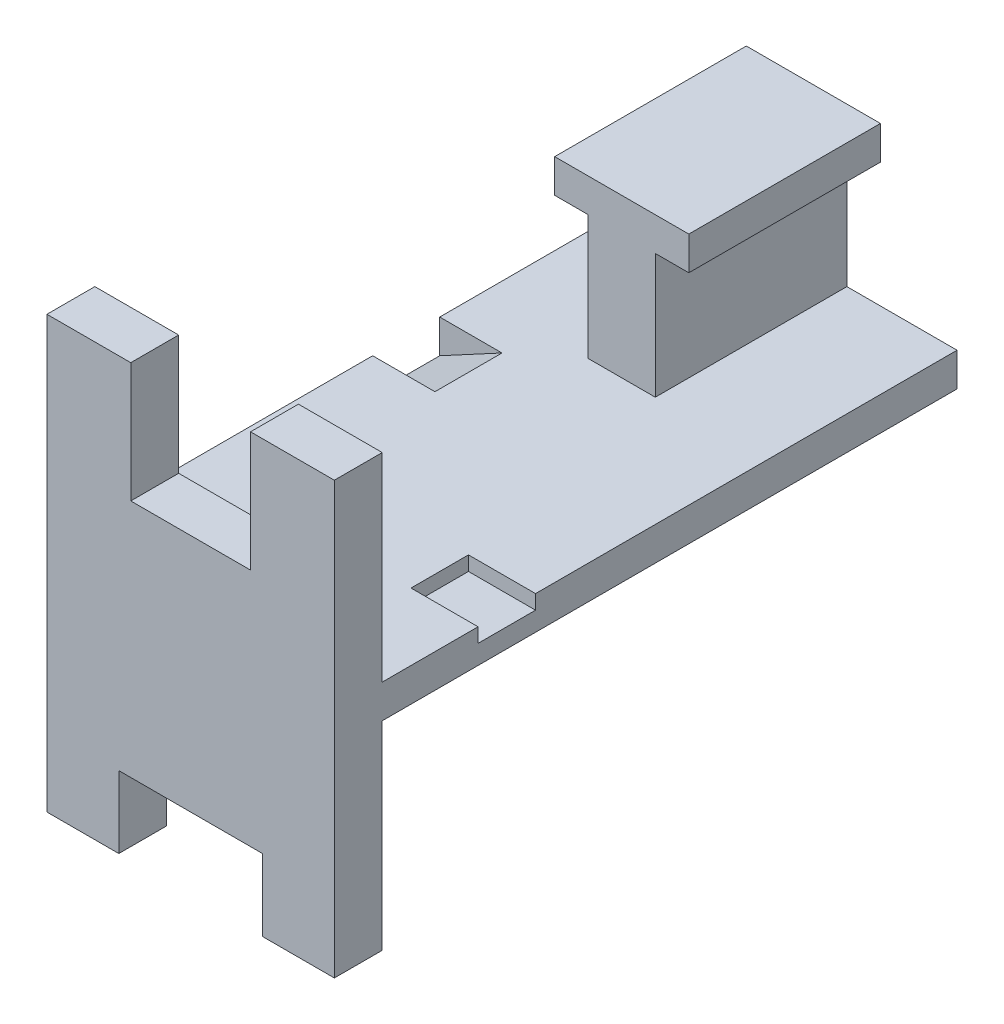
SolidWorks part; units mm, degrees
ref_plane "Спереди" through (0, 0, 0) normal (0, 0, 1) x (1, 0, 0)
ref_plane "Сверху" through (0, 0, 0) normal (0, 1, 0) x (1, 0, 0)
ref_plane "Справа" through (0, 0, 0) normal (1, 0, 0) x (0, 0, -1)
sketch "Эскиз1" plane through (0, 0, 0) normal (0, 0, 1) x (1, 0, 0)
  line L0 (7, 33) -> (23, 33)
  line L1 (0, 0) -> (30, 0)
  line L2 (0, 0) -> (0, 40)
  line L3 (0, 40) -> (30, 40)
  line L4 (30, 0) -> (30, 40)
  line L5 (23, 7) -> (23, 33)
  line L6 (7, 7) -> (23, 7)
  line L7 (7, 7) -> (7, 33)
  line L8 (23, 7) -> (30, 7)
  line L9 (14, 33) -> (14, 40)
  dimension "D1" = 30
  dimension "D2" = 40
  dimension "D4" = 7
  dimension "D3" = 7
extrude "Бобышка-Вытянуть1" add sketch "Эскиз1" along normal blind 120 contours L0 L9 L3 L2 L1 L4 L8 L6 L7
sketch "Эскиз3" plane through (0, 40, 0) normal (0, 1, 0) x (1, 0, 0)
  line L0 (14, -120) -> (14, 0) construction
  line L1 (0, -120) -> (14, -120)
  line L2 (0, -120) -> (0, -40)
  line L3 (0, -40) -> (14, -40)
  line L4 (14, -120) -> (14, -40)
  line L6 (0, 0) -> (14, 0) construction
  dimension "D1" = 40
extrude "Вырез-Вытянуть1" cut sketch "Эскиз3" against normal up to surface (33 mm away) up to face at (18.5, 7, 60)
mirror "Зеркальное отражение1" about plane through (0, 0, 120) normal (-1, 0, 0) of "Вырез-Вытянуть1", "Бобышка-Вытянуть1"
sketch "Эскиз4" plane through (0, 0, 120) normal (0, 0, 1) x (1, 0, 0)
  line L0 (-30, 3.5) -> (30, 3.5) construction
  line L1 (-30, 0) -> (-30, 7) construction
  line L2 (30, 0) -> (30, 7) construction
  line L4 (-30, -41.5) -> (30, -41.5)
  line L5 (-30, -41.5) -> (-30, 48.5)
  line L6 (-30, 48.5) -> (30, 48.5)
  line L7 (30, -41.5) -> (30, 48.5)
  line L8 (-30, -41.5) -> (30, 48.5) construction
  line L9 (-30, 48.5) -> (30, -41.5) construction
  line L10 (-12.5, 23.5) -> (12.5, 23.5)
  line L11 (-12.5, 23.5) -> (-12.5, 48.5)
  line L12 (-12.5, 48.5) -> (12.5, 48.5)
  line L13 (12.5, 23.5) -> (12.5, 48.5)
  line L14 (-12.5, 23.5) -> (12.5, 48.5) construction
  line L15 (-12.5, 48.5) -> (12.5, 23.5) construction
  line L16 (-15, -26.5) -> (15, -26.5)
  line L17 (-15, -26.5) -> (-15, -41.5)
  line L18 (-15, -41.5) -> (15, -41.5)
  line L19 (15, -26.5) -> (15, -41.5)
  line L20 (-15, -26.5) -> (15, -41.5) construction
  line L21 (-15, -41.5) -> (15, -26.5) construction
  point P6 (0, 3.5)
  point P11 (0, 36)
  point P16 (0, -34)
  line M1 (30, 7) -> (-30, 7)
  line M2 (-30, 7) -> (-30, 0)
  line M3 (-30, 0) -> (30, 0)
  line M4 (30, 0) -> (30, 7)
  dimension "D1" = 90
  dimension "D2" = 25
  dimension "D3" = 25
  dimension "D4" = 30
  dimension "D5" = 15
extrude "Бобышка-Вытянуть3" add sketch "Эскиз4" along normal blind 10 contours L16 L19 L4 L7 L5 L17 M3 | L13 L10 L11 L6 L5 L7 M1 | M4 M1 M2 M3
sketch "Эскиз5" plane through (0, 7, 0) normal (0, 1, 0) x (1, 0, 0)
  line L0 (30, -120) -> (30, 0) construction
  line L1 (30, -100) -> (16, -100)
  line L2 (30, -100) -> (30, -88)
  line L3 (30, -88) -> (16, -88)
  line L4 (16, -100) -> (16, -88)
  line L5 (-12.5, -130) -> (12.5, -130) construction
  dimension "D1" = 12
  dimension "D2" = 30
  dimension "D3" = 14
extrude "Вырез-Вытянуть2" cut sketch "Эскиз5" against normal blind 3
sketch "Эскиз6" plane through (0, 0, 0) normal (0, 0, -1) x (-1, 0, 0)
  line L0 (30, 0) -> (17, 7)
  line L1 (7, 7) -> (30, 7) construction
  line L2 (17, 7) -> (30, 7)
  line L3 (30, 7) -> (30, 0)
  dimension "D1" = 13
extrude "Вырез-Вытянуть3" cut sketch "Эскиз6" against normal blind 14 from offset 48
